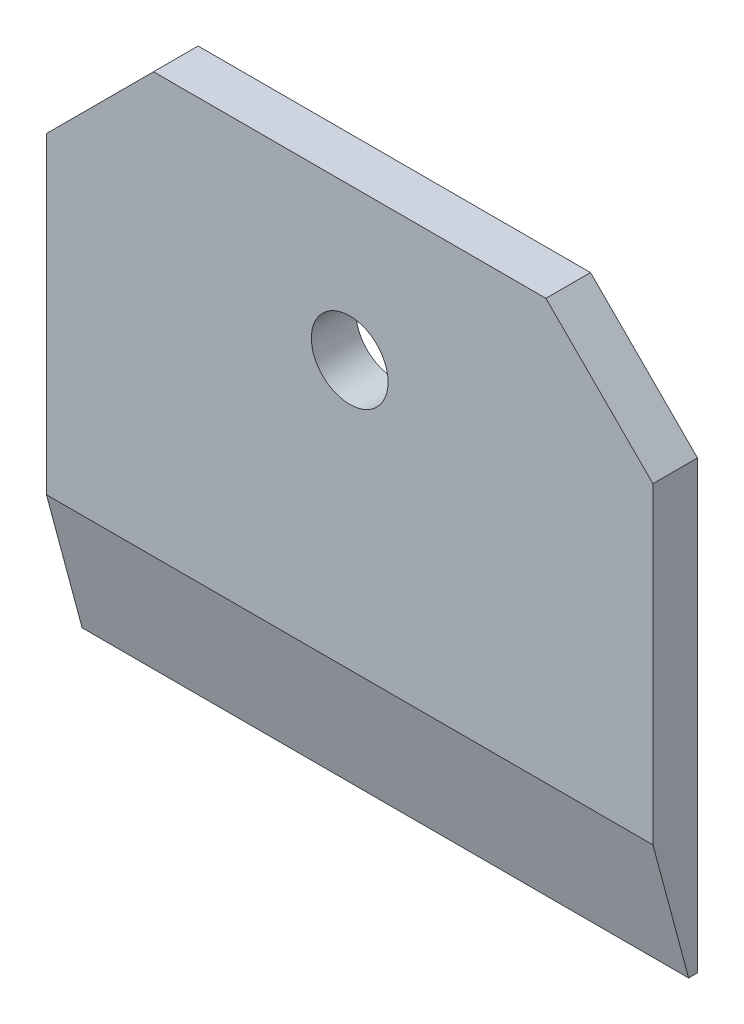
SolidWorks part; units mm, degrees
other "Detailelement1"
other "Detailelement2"
other "Detailelement3"
other "Detailelement4"
material "ZX-100K"
ref_plane "Vorne" through (0, 0, 0) normal (0, 0, 1) x (1, 0, 0)
ref_plane "Oben" through (0, 0, 0) normal (0, 1, 0) x (1, 0, 0)
ref_plane "Rechts" through (0, 0, 0) normal (1, 0, 0) x (0, 0, -1)
sketch "Skizze1" plane through (0, 0, 0) normal (0, 0, 1) x (1, 0, 0)
  line L0 (-34, 50) -> (-22, 62)
  line L1 (-34, 0) -> (34, 0)
  line L2 (-34, 0) -> (-34, 50)
  line L3 (-22, 62) -> (22, 62)
  line L4 (34, 0) -> (34, 50)
  line L5 (22, 62) -> (34, 50)
  point P1 (34, 62)
  point P2 (-34, 62)
  point P8 (0, 0)
  dimension "D1" = 68
  dimension "D2" = 62
extrude "Aufsatz-Linear austragen1" add sketch "Skizze1" along normal blind 5
hole_wizard "Ø8.6 (8.6) Durchmesser Bohrung1" positions "Skizze3" profile "Skizze2" hole size "Ø8.6" standard "Gabler-Normteile"
sketch "Skizze3" plane through (0, 0, 5) normal (0, 0, 1) x (1, 0, 0)
  line L0 (22, 62) -> (-22, 62) construction
  point P0 (0, 45)
  dimension "D1" = 17
sketch "Skizze2" plane through (0, 45, 5) normal (1, 0, 0) x (0, -1, 0)
  line L0 (0, 0) -> (0, 82.5837)
  line L1 (0, 82.5837) -> (4.3, 80)
  line L2 (4.3, 80) -> (4.3, 0)
  line L5 (4.3, 0) -> (0, 0)
  line L10 (0, 82.5837) -> (-4.3, 80) construction
  line L11 (0, -6.35) -> (0, 107.95) construction
  dimension "Bohrerdurchmesser" = 8.6
  dimension "Bohrungstiefe" = 80
  dimension "Spitzenwinkel" = 118
chamfer "Fase1" distance 4 angle 75 1 edges at (0, 0, 5)
